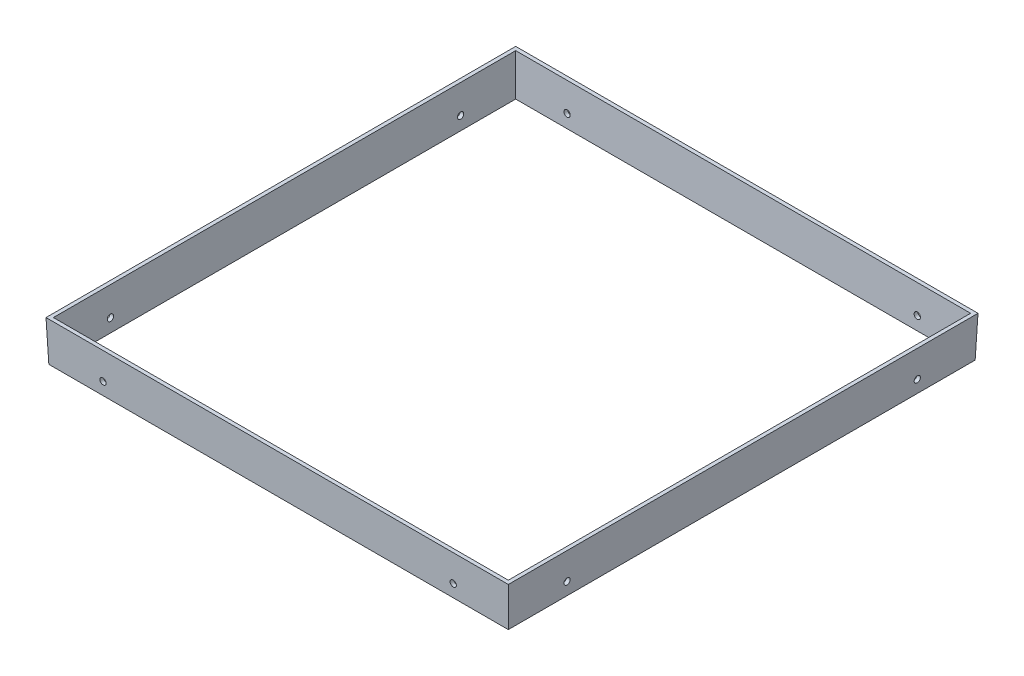
SolidWorks part; units mm, degrees
ref_plane "Front Plane" through (0, 0, 0) normal (0, 0, 1) x (1, 0, 0)
ref_plane "Top Plane" through (0, 0, 0) normal (0, 1, 0) x (1, 0, 0)
ref_plane "Right Plane" through (0, 0, 0) normal (1, 0, 0) x (0, 0, -1)
sketch "Sketch2" plane through (0, 0, 0) normal (0, 1, 0) x (1, 0, 0)
  line L0 (-124.65, -126.65) -> (124.65, -126.65)
  line L1 (-124.65, -126.65) -> (-124.65, 126.65)
  line L2 (-124.65, 126.65) -> (124.65, 126.65)
  line L3 (124.65, -126.65) -> (124.65, 126.65)
  line L4 (-124.65, -126.65) -> (124.65, 126.65) construction
  line L5 (-124.65, 126.65) -> (124.65, -126.65) construction
  point P0 (0, 0)
  point P6 (0, 0)
  dimension "D1" = 249.3
  dimension "D2" = 253.3
extrude "Boss-Extrude1" add sketch "Sketch2" along normal blind 22 draft 2 draft outward yes
shell "Shell1" thickness 2
sketch "Sketch4" plane through (124.4982, -4.3476, 0) normal (0.9994, -0.0349, 0) x (0, 0, -1)
  line L0 (0, 79.377) -> (0, -69.6669) construction
  line L1 (-125.417, 26.2938) -> (125.417, 26.2938) construction
  circle A0 centre (-95, 11.2938) radius 1.7
  circle A1 centre (95, 11.2938) radius 1.7
  dimension "D1" = 3.4
  dimension "D2" = 95
  dimension "D3" = 15
extrude "Cut-Extrude1" cut sketch "Sketch4" along direction (1, 0, 0) on the side against the normal blind 292
sketch "Sketch5" plane through (0, -4.4173, -126.4957) normal (0, -0.0349, -0.9994) x (-1, 0, 0)
  line L0 (-123.417, 26.3636) -> (123.417, 26.3636) construction
  line L1 (0, 42.355) -> (0, -57.1183) construction
  circle A0 centre (-95, 11.3636) radius 1.7
  circle A1 centre (95, 11.3636) radius 1.7
  dimension "D1" = 3.4
  dimension "D2" = 95
  dimension "D3" = 15
extrude "Cut-Extrude2" cut sketch "Sketch5" along direction (0, 0, -1) on the side against the normal blind 292
